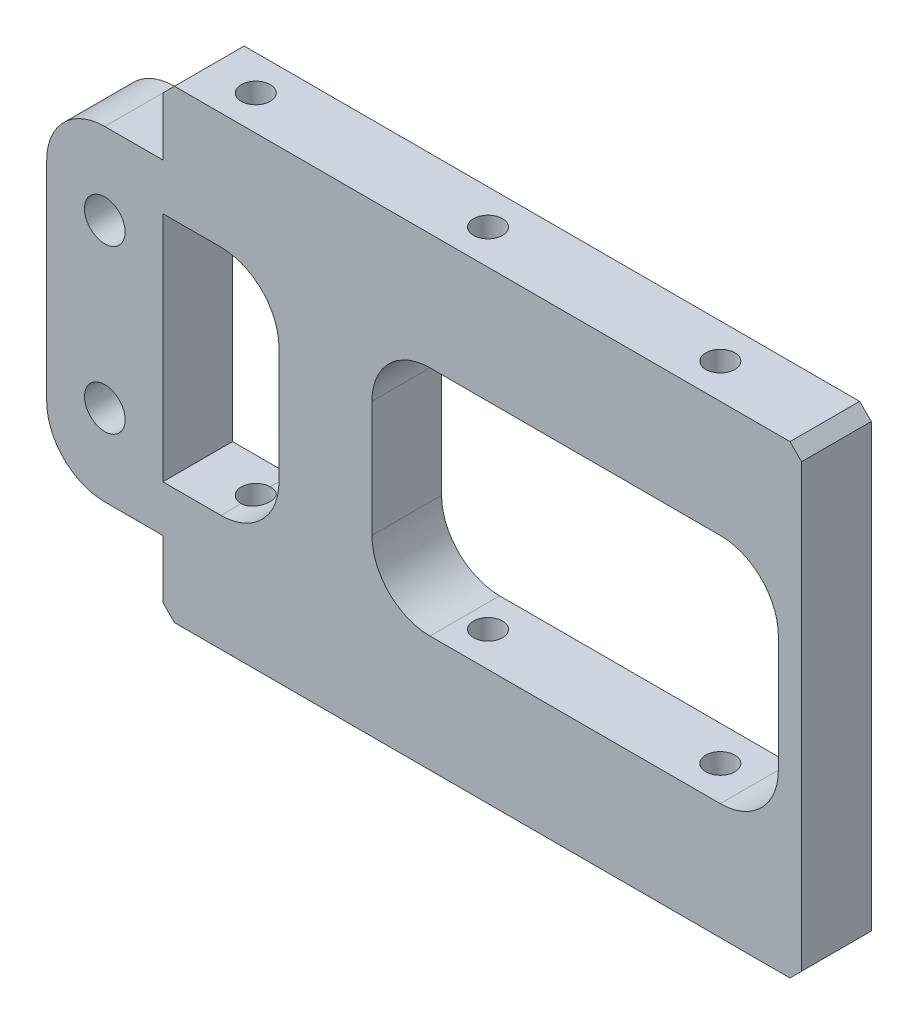
SolidWorks part; units mm, degrees
ref_plane "Front Plane" through (0, 0, 0) normal (0, 0, 1) x (1, 0, 0)
ref_plane "Top Plane" through (0, 0, 0) normal (0, 1, 0) x (1, 0, 0)
ref_plane "Right Plane" through (0, 0, 0) normal (1, 0, 0) x (0, 0, -1)
sketch "Sketch3" plane through (0, 0, 0) normal (0, 1, 0) x (1, 0, 0)
  line L1 (-27.5, 3) -> (27.5, 3)
  line L2 (-27.5, 3) -> (-27.5, -3)
  line L3 (-27.5, -3) -> (27.5, -3)
  line L4 (27.5, 3) -> (27.5, -3)
  line L5 (-27.5, 3) -> (27.5, -3) construction
  line L6 (-27.5, -3) -> (27.5, 3) construction
  point P0 (1.8927, -1.1648)
  dimension "D1" = 6
  dimension "D2" = 55
extrude "Boss-Extrude1" add sketch "Sketch3" along normal blind 40
sketch "Sketch4" plane through (0, 40, 0) normal (0, 1, 0) x (1, 0, 0)
  line L0 (-27.5, 3) -> (-27.5, -3) construction
  line L1 (-55, 0) -> (55, 0) construction
  point P0 (-22.5, 0)
  point P1 (-2.5, 0)
  point P2 (17.5, 0)
  dimension "D1" = 5
  dimension "D2" = 20
  dimension "D3" = 20
hole_wizard "M3x0.5 Tapped Hole1" positions "Sketch4" profile "Sketch5" tap size "M3x0.5" standard "ANSI Metric" end condition through all
sketch "Sketch5" plane through (-22.5, 40, 0) normal (1, 0, 0) x (0, 0, 1)
  line L0 (0, 0) -> (0, 40)
  line L1 (0, 40) -> (1.25, 40)
  line L2 (1.25, 40) -> (1.25, 0)
  line L5 (1.25, 0) -> (0, 0)
  line L11 (0, -6.35) -> (0, 107.95) construction
  dimension "Thru Tap Drill Dia." = 2.5
  dimension "Thru Tap Drill Depth" = 40
cosmetic thread "Hole Thread1" parameters "D2"=3
cosmetic thread "Hole Thread2" parameters "D2"=3
cosmetic thread "Hole Thread3" parameters "D2"=3
sketch "Sketch6" plane through (0, 0, 3) normal (0, 0, 1) x (1, 0, 0)
  line L0 (-27.5, 40) -> (-27.5, 0) construction
  line L1 (-27.5, 30) -> (-22.5, 30)
  line L2 (-27.5, 30) -> (-27.5, 10)
  line L3 (-27.5, 10) -> (-22.5, 10)
  line L4 (-17.5, 25) -> (-17.5, 15)
  line L5 (-4.5, 30) -> (20.5, 30)
  line L6 (-9.5, 25) -> (-9.5, 15)
  line L7 (-4.5, 10) -> (20.5, 10)
  line L8 (25.5, 25) -> (25.5, 15)
  line L9 (55, 0) -> (-55, 0) construction
  line L10 (-27.5, 40) -> (27.5, 40) construction
  arc A0 (20.5, 10) -> (25.5, 15) centre (20.5, 15) ccw
  arc A1 (-9.5, 15) -> (-4.5, 10) centre (-4.5, 15) ccw
  arc A2 (20.5, 30) -> (25.5, 25) centre (20.5, 25) cw
  arc A3 (-4.5, 30) -> (-9.5, 25) centre (-4.5, 25) ccw
  arc A4 (-22.5, 10) -> (-17.5, 15) centre (-22.5, 15) ccw
  arc A5 (-22.5, 30) -> (-17.5, 25) centre (-22.5, 25) cw
  point P16 (25.5, 10)
  point P19 (-9.5, 10)
  point P26 (-17.5, 10)
  dimension "D6" = 5
  dimension "D7" = 5
  dimension "D1" = 10
  dimension "D2" = 10
  dimension "D3" = 10
  dimension "D4" = 8
  dimension "D5" = 35
extrude "Cut-Extrude1" cut sketch "Sketch6" against normal blind 10
chamfer "Chamfer1" distance 1 angle 45 4 edges at (27.5, 0, 0) (27.5, 40, 0) (-27.5, 0, 0) (-27.5, 40, 0)
sketch "Sketch7" plane through (0, 0, 3) normal (0, 0, 1) x (1, 0, 0)
  line L0 (-27.5, 39) -> (-27.5, 30) construction
  line L1 (-27.5, 34) -> (-32.5, 34)
  line L2 (-27.5, 34) -> (-27.5, 6)
  line L3 (-27.5, 6) -> (-32.5, 6)
  line L4 (-37.5, 29) -> (-37.5, 11)
  line L5 (-26.5, 40) -> (26.5, 40) construction
  line L6 (55, 0) -> (-55, 0) construction
  line L8 (-17.5, 15) -> (-17.5, 25) construction
  arc A0 (-32.5, 34) -> (-37.5, 29) centre (-32.5, 29) ccw
  arc A1 (-32.5, 6) -> (-37.5, 11) centre (-32.5, 11) cw
  circle A2 centre (-32.5, 27) radius 1.75
  circle A3 centre (-32.5, 13) radius 1.75
  point P14 (-37.5, 6)
  point P21 (-17.5, 20)
  point P22 (-35, 13)
  dimension "D4" = 5
  dimension "D5" = 3.5
  dimension "D1" = 6
  dimension "D2" = 6
  dimension "D3" = 10
  dimension "D6" = 7
  dimension "D7" = 14
  dimension "D8" = 5
extrude "Boss-Extrude2" add sketch "Sketch7" against normal blind 6
